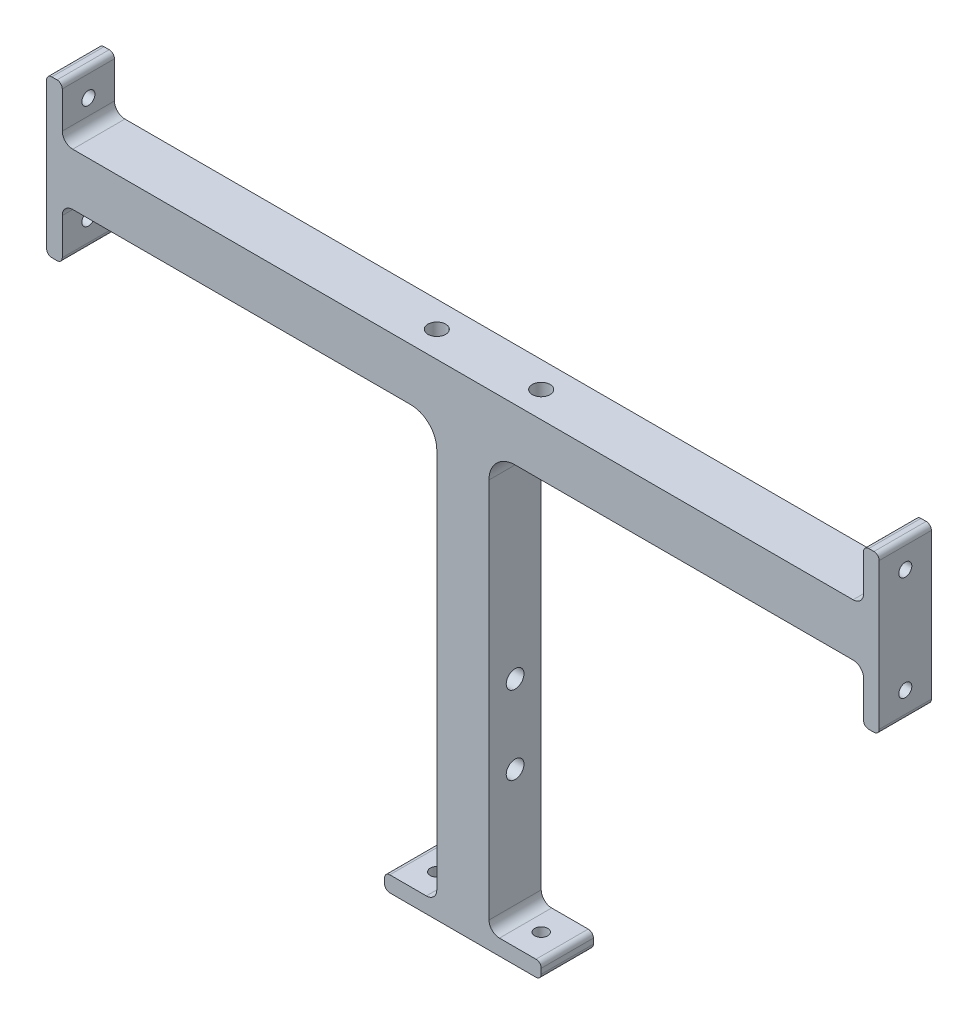
SolidWorks part; units mm, degrees
material "PLA"
ref_plane "Front Plane" through (0, 0, 0) normal (0, 0, 1) x (1, 0, 0)
ref_plane "Top Plane" through (0, 0, 0) normal (0, 1, 0) x (1, 0, 0)
ref_plane "Right Plane" through (0, 0, 0) normal (1, 0, 0) x (0, 0, -1)
sketch "Sketch1" plane through (0, 0, 0) normal (0, 0, 1) x (1, 0, 0)
  line L0 (19.05, 0) -> (-19.05, 0)
  line L1 (-19.05, 0) -> (-19.05, 3.81)
  line L2 (-19.05, 3.81) -> (-6.35, 3.81)
  line L3 (-6.35, 3.81) -> (-6.35, 105.41)
  line L4 (-6.35, 105.41) -> (-97.4598, 105.41)
  line L5 (-97.4598, 105.41) -> (-97.4598, 92.71)
  line L6 (-97.4598, 92.71) -> (-101.2698, 92.71)
  line L7 (-101.2698, 92.71) -> (-101.2698, 130.81)
  line L8 (-101.2698, 130.81) -> (-97.4598, 130.81)
  line L9 (-97.4598, 130.81) -> (-97.4598, 118.11)
  line L10 (-97.4598, 118.11) -> (97.4598, 118.11)
  line L11 (0, 118.11) -> (0, 0) construction
  line L12 (97.4598, 130.81) -> (97.4598, 118.11)
  line L13 (101.2698, 130.81) -> (97.4598, 130.81)
  line L14 (101.2698, 92.71) -> (101.2698, 130.81)
  line L15 (97.4598, 92.71) -> (101.2698, 92.71)
  line L16 (97.4598, 105.41) -> (97.4598, 92.71)
  line L17 (6.35, 105.41) -> (97.4598, 105.41)
  line L18 (6.35, 3.81) -> (6.35, 105.41)
  line L19 (19.05, 3.81) -> (6.35, 3.81)
  line L20 (19.05, 0) -> (19.05, 3.81)
  dimension "D1" = 12.7
  dimension "D2" = 12.7
  dimension "D3" = 3.81
  dimension "D4" = 3.81
  dimension "D5" = 12.7
  dimension "D6" = 3.81
  dimension "D7" = 101.6
  dimension "D8" = 12.7
  dimension "D9" = 202.5396
extrude "Boss-Extrude1" add sketch "Sketch1" along normal blind 12.7
sketch "Sketch2" plane through (101.2698, 0, 0) normal (1, 0, 0) x (0, 0, -1)
  line L0 (-12.7, 111.76) -> (0, 111.76) construction
  line L1 (-12.7, 92.71) -> (-12.7, 130.81) construction
  line L2 (0, 92.71) -> (0, 130.81) construction
  line L3 (-6.35, 111.76) -> (-6.35, 130.81) construction
  line L4 (-12.7, 130.81) -> (0, 130.81) construction
  circle A0 centre (-6.35, 124.46) radius 1.5875
  circle A1 centre (-6.35, 99.06) radius 1.5875
  dimension "D1" = 3.175
  dimension "D3" = 124.46
  dimension "D2" = 12.7
  dimension "D4" = 99.06
extrude "Side-Mount-Holes" cut sketch "Sketch2" against normal blind 6.35
mirror "Mirror1" about plane through (0, 0, 0) normal (1, 0, 0) of "Side-Mount-Holes"
sketch "Sketch3" plane through (0, 0, 0) normal (0, -1, 0) x (1, 0, 0)
  line L0 (19.05, 6.35) -> (-19.05, 6.35) construction
  line L1 (19.05, 12.7) -> (19.05, 0) construction
  line L2 (-19.05, 12.7) -> (-19.05, 0) construction
  line L3 (0, 0) -> (0, 12.7) construction
  line L4 (-19.05, 12.7) -> (19.05, 12.7) construction
  circle A0 centre (12.7, 6.35) radius 1.5875
  circle A1 centre (-12.7, 6.35) radius 1.5875
  dimension "D1" = 3.175
  dimension "D2" = 12.7
extrude "Bottom_Mount_Holes" cut sketch "Sketch3" against normal up to surface (3.81 mm away) up to face at (-12.7, 3.81, 6.35)
fillet "Fillet1" radius 6.35 2 edges at (6.35, 105.41, 6.35) (-6.35, 105.41, 6.35)
fillet "Fillet2" radius 2.54 6 edges at (-6.35, 3.81, 6.35) (6.35, 3.81, 6.35) (-97.4598, 105.41, 6.35) (-97.4598, 118.11, 6.35) (97.4598, 105.41, 6.35) (97.4598, 118.11, 6.35)
sketch "Sketch4" plane through (6.35, 0, 0) normal (1, 0, 0) x (0, 0, -1)
  line L0 (-12.7, 44.45) -> (0, 44.45) construction
  line L1 (-12.7, 6.35) -> (-12.7, 99.06) construction
  line L2 (0, 6.35) -> (0, 99.06) construction
  line L3 (-6.35, 44.45) -> (-6.35, 53.975) construction
  line L4 (-12.7, 0) -> (0, 0) construction
  circle A0 centre (-6.35, 53.975) radius 2.159
  circle A1 centre (-6.35, 34.925) radius 2.159
  dimension "D1" = 4.318
  dimension "D2" = 19.05
  dimension "D3" = 44.45
extrude "Switch_Mount_Holes" cut sketch "Sketch4" against normal blind 7.112
sketch "Sketch5" plane through (0, 118.11, 0) normal (0, 1, 0) x (1, 0, 0)
  line L0 (0, 0) -> (0, -12.7) construction
  line L1 (94.9198, -12.7) -> (-94.9198, -12.7) construction
  line L2 (0, -6.35) -> (-12.7, -6.35) construction
  circle A0 centre (-12.7, -6.35) radius 2.159
  circle A1 centre (12.7, -6.35) radius 2.159
  dimension "D1" = 4.318
  dimension "D2" = 25.4
extrude "Cut-Extrude1" cut sketch "Sketch5" against normal blind 7.112
fillet "Fillet3" radius 1.27 12 edges at (101.2698, 130.81, 6.35) (97.4598, 130.81, 6.35) (101.2698, 92.71, 6.35) (97.4598, 92.71, 6.35) (19.05, 3.81, 6.35) (19.05, 0, 6.35) (-19.05, 3.81, 6.35) (-19.05, 0, 6.35) (-97.4598, 92.71, 6.35) (-101.2698, 92.71, 6.35) (-97.4598, 130.81, 6.35) (-101.2698, 130.81, 6.35)
equation "\"D4@Sketch1\"=\"D3@Sketch1\""
equation "\"D6@Sketch1\"=\"D3@Sketch1\""
